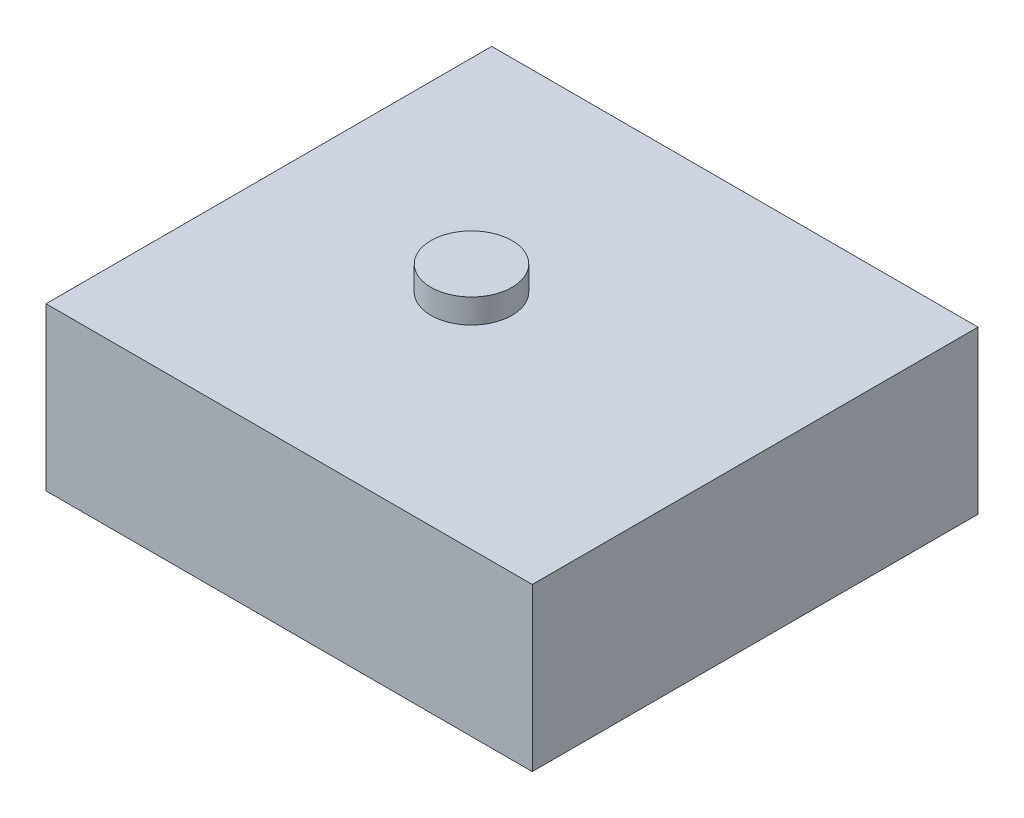
SolidWorks part; units mm, degrees
ref_plane "Front Plane" through (0, 0, 0) normal (0, 0, 1) x (1, 0, 0)
ref_plane "Top Plane" through (0, 0, 0) normal (0, 1, 0) x (1, 0, 0)
ref_plane "Right Plane" through (0, 0, 0) normal (1, 0, 0) x (0, 0, -1)
sketch "Sketch1" plane through (0, 0, 0) normal (0, 1, 0) x (1, 0, 0)
  line L1 (-60, 55) -> (60, 55)
  line L2 (-60, 55) -> (-60, -55)
  line L3 (-60, -55) -> (60, -55)
  line L4 (60, 55) -> (60, -55)
  line L5 (-60, 55) -> (60, -55) construction
  line L6 (-60, -55) -> (60, 55) construction
  point P0 (0, 0)
  dimension "D1" = 110
  dimension "D2" = 120
extrude "Boss-Extrude1" add sketch "Sketch1" along normal blind 40
sketch "Sketch2" plane through (0, 40, 0) normal (0, 1, 0) x (1, 0, 0)
  line L0 (0, 0) -> (-50000, 0) construction
  line L1 (0, 0) -> (0, -50000) construction
  line L2 (-60, 55) -> (-60, -55) construction
  circle A0 centre (-10, 0) radius 10
  dimension "D1" = 10
  dimension "D2" = 50
extrude "Boss-Extrude2" add sketch "Sketch2" along normal blind 6
